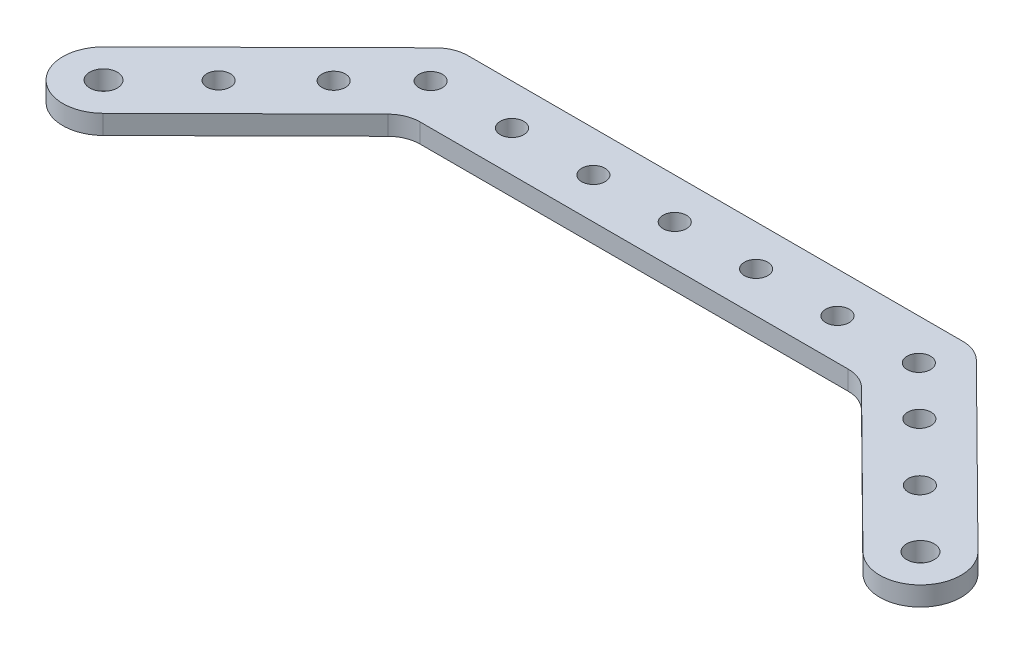
SolidWorks part; units mm, degrees
material "Custom Plastic"
ref_plane "Front Plane" through (0, 0, 0) normal (0, 0, 1) x (1, 0, 0)
ref_plane "Top Plane" through (0, 0, 0) normal (0, 1, 0) x (1, 0, 0)
ref_plane "Right Plane" through (0, 0, 0) normal (1, 0, 0) x (0, 0, -1)
sketch "Sketch1" plane through (0, 0, 0) normal (0, 1, 0) x (1, 0, 0)
  line L1 (70.104, -19.05) -> (-70.104, -19.05)
  line L2 (70.104, -19.05) -> (70.104, 19.05)
  line L3 (70.104, 19.05) -> (-70.104, 19.05)
  line L4 (-70.104, -19.05) -> (-70.104, 19.05)
  line L5 (70.104, -19.05) -> (-70.104, 19.05) construction
  line L6 (70.104, 19.05) -> (-70.104, -19.05) construction
  point P0 (0, 0)
  dimension "D1" = 140.208
  dimension "D2" = 38.1
extrude "Boss-Extrude1" add sketch "Sketch1" along normal blind 3
sketch "Sketch2" plane through (0, 3, 0) normal (0, 1, 0) x (1, 0, 0)
  line L0 (-59.2863, -17.2124) -> (-35.4882, 6.35)
  line L1 (-35.4882, 6.35) -> (35.4882, 6.35)
  line L2 (35.4882, 6.35) -> (59.2863, -17.2124)
  line L3 (59.2863, -17.2124) -> (68.2217, -8.1876) construction
  line L4 (68.2217, -8.1876) -> (40.7118, 19.05)
  line L5 (70.104, 19.05) -> (-70.104, 19.05) construction
  line L6 (40.7118, 19.05) -> (-40.7118, 19.05)
  line L8 (-40.7118, 19.05) -> (-68.2217, -8.1876)
  line L9 (-68.2217, -8.1876) -> (-59.2863, -17.2124) construction
  line L10 (0, 0) -> (0, 6.35) construction
  line L11 (0, 6.35) -> (0, 19.05) construction
  line L12 (-70.104, 19.05) -> (-70.104, -19.05) construction
  line L13 (-70.104, -19.05) -> (70.104, -19.05) construction
  line L14 (-63.754, -12.7) -> (-54.7292, -3.7645) construction
  line L15 (-54.7292, -3.7645) -> (-45.7044, 5.1709) construction
  line L17 (-45.7044, 5.1709) -> (-38.1, 12.7) construction
  line L18 (-38.1, 12.7) -> (-38.1, 19.05) construction
  line L19 (-38.1, 12.7) -> (-38.1, 6.35) construction
  line L20 (-38.1, 12.7) -> (-25.4, 12.7) construction
  line L21 (-25.4, 12.7) -> (-12.7, 12.7) construction
  line L22 (-12.7, 12.7) -> (0, 12.7) construction
  line L23 (0, 12.7) -> (12.7, 12.7) construction
  line L24 (12.7, 12.7) -> (25.4, 12.7) construction
  line L25 (45.7044, 5.1709) -> (38.1, 12.7) construction
  line L27 (54.7292, -3.7645) -> (45.7044, 5.1709) construction
  line L28 (63.754, -12.7) -> (54.7292, -3.7645) construction
  line L29 (25.4, 12.7) -> (38.1, 12.7) construction
  arc A0 (-68.2217, -8.1876) -> (-59.2863, -17.2124) centre (-63.754, -12.7) ccw
  arc A1 (68.2217, -8.1876) -> (59.2863, -17.2124) centre (63.754, -12.7) cw
  point P34 (0, 12.7)
  dimension "D1" = 12.7
  dimension "D3" = 12.7
extrude "Cut-Extrude1" cut sketch "Sketch2" against normal through all flip side to cut
hole_wizard "#8 Clearance Hole1" positions "Sketch7" profile "Sketch6" hole size "#8" standard "ANSI Inch" end condition through all
sketch "Sketch7" plane through (0, 3, 0) normal (0, 1, 0) x (1, 0, 0)
  point P8 (-63.754, -12.7)
  point P11 (63.754, -12.7)
sketch "Sketch6" plane through (-63.754, 3, 12.7) normal (1, 0, 0) x (0, 0, 1)
  line L0 (0, 0) -> (0, 3)
  line L1 (0, 3) -> (2.1526, 3)
  line L2 (2.1526, 3) -> (2.1526, 0)
  line L5 (2.1526, 0) -> (0, 0)
  line L11 (0, -6.35) -> (0, 107.95) construction
  dimension "Thru Hole Dia." = 4.3053
  dimension "Thru Hole Depth" = 3
hole_wizard "#6 Clearance Hole1" positions "Sketch9" profile "Sketch8" hole size "#6" standard "ANSI Inch" end condition through all
sketch "Sketch9" plane through (0, 3, 0) normal (0, 1, 0) x (1, 0, 0)
  point P0 (-54.7292, -3.7645)
  point P3 (-45.7044, 5.1709)
  point P6 (-45.7044, 5.1709)
  point P9 (-38.1, 12.7)
  point P18 (0, 12.7)
  point P27 (38.1, 12.7)
  point P30 (45.7044, 5.1709)
  point P36 (54.7292, -3.7645)
  point P46 (-25.4, 12.7)
  point P49 (-12.7, 12.7)
  point P52 (12.7, 12.7)
  point P55 (25.4, 12.7)
sketch "Sketch8" plane through (-54.7292, 3, 3.7645) normal (1, 0, 0) x (0, 0, 1)
  line L0 (0, 0) -> (0, 3)
  line L1 (0, 3) -> (1.8288, 3)
  line L2 (1.8288, 3) -> (1.8288, 0)
  line L5 (1.8288, 0) -> (0, 0)
  line L11 (0, -6.35) -> (0, 107.95) construction
  dimension "Thru Hole Dia." = 3.6576
  dimension "Thru Hole Depth" = 3
fillet "Fillet1" radius 5.08 4 edges at (-40.7118, 1.5, -19.05) (40.7118, 1.5, -19.05) (35.4882, 1.5, -6.35) (-35.4882, 1.5, -6.35)
